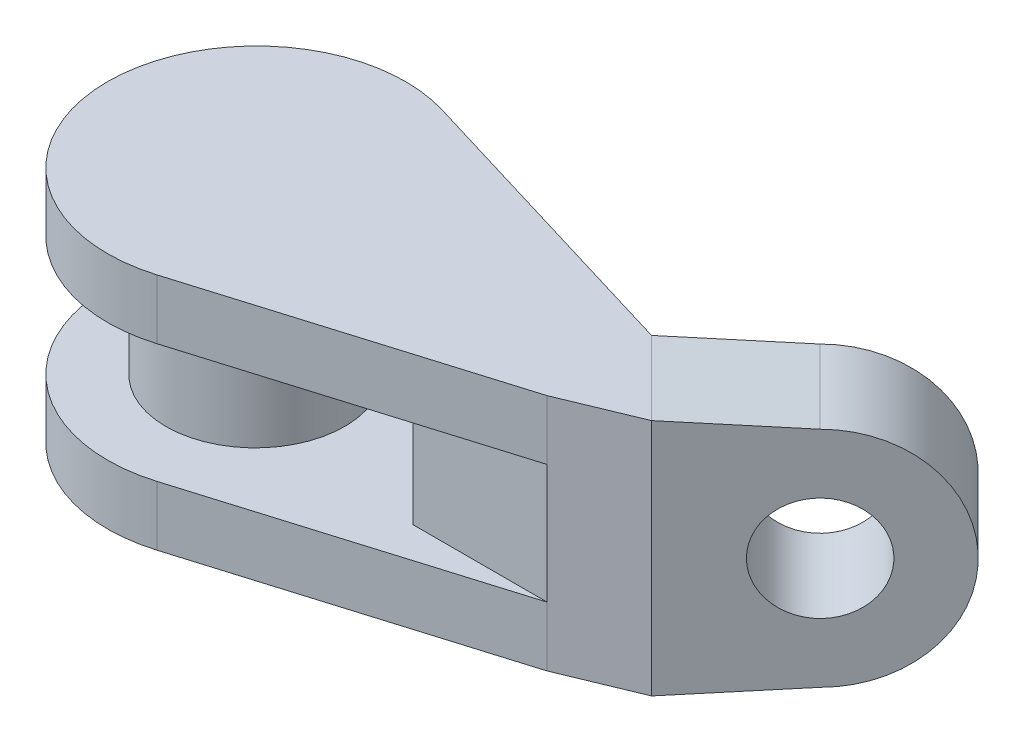
SolidWorks part; units mm, degrees
ref_plane "Front Plane" through (0, 0, 0) normal (0, 0, 1) x (1, 0, 0)
ref_plane "Top Plane" through (0, 0, 0) normal (0, 1, 0) x (1, 0, 0)
ref_plane "Right Plane" through (0, 0, 0) normal (1, 0, 0) x (0, 0, -1)
sketch "Sketch1" plane through (0, 0, 0) normal (0, 0, 1) x (1, 0, 0)
  line L0 (0, -20) -> (70, -20)
  line L1 (0, -40) -> (100, -40)
  line L2 (0, -40) -> (0, -20)
  line L3 (0, 40) -> (100, 40)
  line L5 (70, -20) -> (70, 20)
  line L6 (70, 20) -> (0, 20)
  line L7 (0, 20) -> (0, 40)
  line L8 (100, -40) -> (115, -40)
  line L9 (100, 40) -> (115, 40)
  line L11 (115, 40) -> (115, -40)
  dimension "D1" = 80
  dimension "D2" = 20
  dimension "D3" = 70
  dimension "20" = 20
  dimension "D4" = 20
  dimension "D5" = 15
extrude "Boss-Extrude1" add sketch "Sketch1" along normal blind 35
sketch "Sketch2" plane through (0, 0, 0) normal (0, 1, 0) x (1, 0, 0)
  line L0 (115, -35) -> (115, 0) construction
  line L1 (115, -35) -> (115, 0)
  line L2 (115, 0) -> (143.2843, 28.2843)
  line L3 (115, -35) -> (160.7843, 10.7843)
  line L4 (160.7843, 10.7843) -> (143.2843, 28.2843)
  dimension "D1" = 135
  dimension "D2" = 40
extrude "Boss-Extrude2" add sketch "Sketch2" along normal up to surface and the other way through all separate body
sketch "Sketch7" plane through (57.5, 0, 57.5) normal (-0.7071, 0, -0.7071) x (-0.7071, 0, 0.7071)
  line L0 (-121.3173, 37.5) -> (-81.3173, 40)
  line L1 (-121.3173, -37.5) -> (-81.3173, -40)
  line L4 (-81.3173, -40) -> (-81.3173, 40)
  line L5 (-81.3173, 40) -> (-121.3173, 40)
  line L6 (-121.3173, 40) -> (-121.3173, -40)
  line L7 (-121.3173, -40) -> (-81.3173, -40)
  line L8 (-81.3173, -40) -> (-81.3173, 40)
  line L12 (-121.3173, 40) -> (-121.3173, -40) construction
  circle A0 centre (-121.3173, 0) radius 17.5
  arc A1 (-121.3173, 37.5) -> (-121.3173, -37.5) centre (-121.3173, 0) ccw
  dimension "D2" = 35
  dimension "D3" = 20
  dimension "D1" = 0
extrude "Boss-Extrude8" add sketch "Sketch7" against normal blind 35 separate body
sketch "Sketch9" plane through (0, 0, 0) normal (0, 1, 0) x (1, 0, 0)
  line L0 (139.7487, -24.7487) -> (115, 0) construction
  line L1 (115, -35) -> (115, 0) construction
  line L2 (139.7487, -24.7487) -> (115, 0)
  line L3 (115, -35) -> (115, 0)
  line L4 (115, -35) -> (139.7487, -24.7487)
extrude "Boss-Extrude9" add sketch "Sketch9" along normal up to surface and the other way up to surface separate body up to face at (57.5, 40, 17.5) other way up to face at (57.5, -40, 17.5)
delete or keep bodies "Body-Delete/Keep 1" type delete bodies bodies 102
sketch "Sketch5" plane through (0, 0, 0) normal (0, 1, 0) x (1, 0, 0)
  line L0 (0, -66) -> (0, 66) construction
  circle A0 centre (0, -17.9432) radius 30
  dimension "D1" = 60
extrude "Boss-Extrude6" add sketch "Sketch5" along normal blind 20 and the other way blind 20 separate body
sketch "Sketch6" plane through (0, 20, 0) normal (0, 1, 0) x (1, 0, 0)
  line L0 (0, -35) -> (0, 0) construction
  line L1 (115, -35) -> (0, -35) construction
  line L2 (115, 0) -> (0, 0) construction
  line L3 (115, -35) -> (46.8375, -35)
  line L4 (115, 0) -> (46.8375, 0)
  line L5 (14.4554, 30.3648) -> (115, 0)
  line L7 (14.4554, -65.3648) -> (115, -35)
  arc A0 (14.4554, 30.3648) -> (14.4554, -65.3648) centre (0, -17.5) ccw
  arc A1 (46.8375, -35) -> (46.8375, 0) centre (0, -17.5) ccw
  dimension "D1" = 100
extrude "Boss-Extrude10" add sketch "Sketch6" along normal up to surface (20 mm away) separate body up to face at (57.5, 40, 17.5)
move or copy body "Body-Move/Copy2" bodies to move or copy 112 copy yes number of copies 1 translate (0, -60, 0)
combine bodies "Combine1" operation type add bodies to combine 112 101 111 110 114 105
